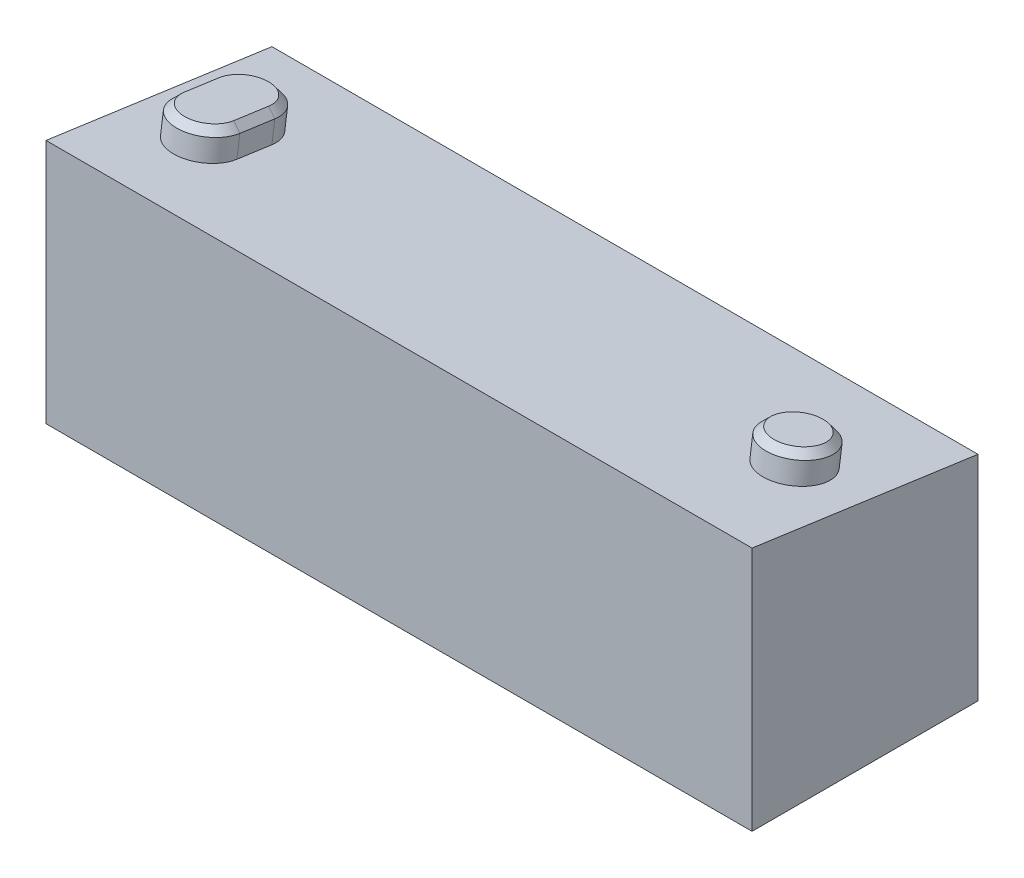
SolidWorks part; units mm, degrees
material "AISI 1010 钢，热轧条材"
ref_plane "前视基准面" through (0, 0, 0) normal (0, 0, 1) x (1, 0, 0)
ref_plane "上视基准面" through (0, 0, 0) normal (0, 1, 0) x (1, 0, 0)
ref_plane "右视基准面" through (0, 0, 0) normal (1, 0, 0) x (0, 0, -1)
sketch "草图1" plane through (0, 0, 0) normal (0, 0, 1) x (1, 0, 0)
  line L0 (-17, 0) -> (-17, -66.8639)
  line L1 (-20.5, 0) -> (-20.5, -66.8639)
  line L2 (-17, -66.8639) -> (-20.5, -66.8639)
  line L3 (0, 4.1737) -> (0, 50004.1737) construction
  line L4 (17, -66.8639) -> (20.5, -66.8639)
  line L5 (20.5, 0) -> (20.5, -66.8639)
  line L6 (17, 0) -> (17, -66.8639)
  arc A0 (17, 0) -> (-17, 0) centre (0, 0) ccw
  arc A1 (20.5, 0) -> (-20.5, 0) centre (0, 0) ccw
  circle A3 centre (0, 0) radius 20.5 construction
  circle A4 centre (0, 0) radius 17 construction
  point P4 (16.2572, 4.9703)
  point P15 (20.5, 0)
  dimension "D1" = 34
  dimension "D2" = 3.5
extrude "凸台-拉伸1" add sketch "草图1" along normal mid plane 32
sketch "草图2" plane through (0, 0, 0) normal (1, 0, 0) x (0, 0, -1)
  line L0 (0, 0) -> (50000, 0) construction
  line L1 (0, 0) -> (0, -50000) construction
  line L2 (29.9617, -44.7108) -> (0, -40.5) construction
  line L3 (16, -42.7487) -> (-16, -38.2513)
  line L4 (16, -66.8639) -> (16, 0) construction
  line L5 (-16, -66.8639) -> (-16, 0) construction
  line L6 (-16, -38.2513) -> (-16, -66.8639)
  line L7 (-16, -66.8639) -> (16, -66.8639)
  line L8 (16, -66.8639) -> (16, -42.7487)
  dimension "D1" = 8
  dimension "D2" = 40.5
extrude "切除-拉伸1" cut sketch "草图2" against normal mid plane 100
sketch "草图3" plane through (-20.5, 0, 0) normal (-1, 0, 0) x (0, 0, 1)
  line L0 (-16, -42.7487) -> (16, -38.2513)
  line L1 (-16, -39.2143) -> (16, -34.717)
  line L4 (-16, -42.7487) -> (-16, -39.2143)
  line L5 (16, -38.2513) -> (16, -34.717)
  line L7 (-16.4871, -39.2827) -> (15.5129, -34.7854) construction
  dimension "D1" = 3.5
extrude "凸台-拉伸2" add sketch "草图3" along normal blind 28.5
mirror "镜向1" about plane through (0, 0, 0) normal (1, 0, 0) of "凸台-拉伸2"
sketch "草图4" plane through (0, -36.2496, 5.0946) normal (0, 0.9903, -0.1392) x (1, 0, 0)
  line L0 (0, 0) -> (0, -50000) construction
  line L1 (-49, 5.1446) -> (49, 5.1446) construction
  line L2 (-49, -11.0126) -> (-49, 21.3019) construction
  line L3 (49, -11.0126) -> (49, 21.3019) construction
  line L4 (-40.5, 21.3019) -> (-40.5, -11.0126) construction
  line L5 (-49, 21.3019) -> (-20.5, 21.3019) construction
  line L6 (-49, -11.0126) -> (-20.5, -11.0126) construction
  line L7 (40.5, 21.3019) -> (40.5, -11.0126) construction
  line L8 (-36, 7.6446) -> (-36, 2.6446)
  line L9 (-45, 7.6446) -> (-45, 2.6446)
  arc A0 (-36, 7.6446) -> (-45, 7.6446) centre (-40.5, 7.6446) ccw
  arc A1 (-45, 2.6446) -> (-36, 2.6446) centre (-40.5, 2.6446) ccw
  circle A2 centre (40.5, 5.1446) radius 4.5
  dimension "D2" = 9
  dimension "D4" = 9
  dimension "D1" = 81
  dimension "D3" = 5
extrude "切除-拉伸2" cut sketch "草图4" against normal blind 28.5
sketch "草图5" plane through (0, 0, 0) normal (1, 0, 0) x (0, 0, -1)
  line L0 (16, -42.7487) -> (-16, -38.2513)
  line L1 (-16, -38.2513) -> (-16, -72.9987)
  line L2 (-16, -72.9987) -> (16, -72.9987)
  line L3 (16, -72.9987) -> (16, -42.7487)
  dimension "D1" = 30.25
extrude "凸台-拉伸3" add sketch "草图5" along normal mid plane 100 separate body
sketch "草图6" plane through (0, -39.7155, 5.5817) normal (0, 0.9903, -0.1392) x (1, 0, 0)
  line L2 (-36, 2.6446) -> (-36, 7.6446)
  line L3 (-36, 2.6446) -> (-36, 7.6446)
  line L4 (0, 0) -> (0, 49.0498) construction
  line L5 (-45, 7.6446) -> (-45, 2.6446)
  line L6 (-45, 7.6446) -> (-45, 2.6446)
  circle A0 centre (40.5, 5.1446) radius 4.5
  arc A2 (-36, 7.6446) -> (-45, 7.6446) centre (-40.5, 7.6446) ccw
  arc A3 (-36, 7.6446) -> (-45, 7.6446) centre (-40.5, 7.6446) ccw
  arc A5 (-45, 2.6446) -> (-36, 2.6446) centre (-40.5, 2.6446) ccw
  arc A6 (-45, 2.6446) -> (-36, 2.6446) centre (-40.5, 2.6446) ccw
  dimension "D1" = 0
  dimension "D2" = 0
  dimension "D3" = 0
  dimension "D4" = 0
extrude "凸台-拉伸4" add sketch "草图6" along normal blind 4
sketch "草图8" plane through (0, 0, 0) normal (1, 0, 0) x (0, 0, -1)
  line L0 (16, -42.7487) -> (-16, -38.2513)
  line L1 (-16, -38.2513) -> (-16, 32.2935)
  line L2 (-16, 32.2935) -> (16, 32.2935)
  line L3 (16, 32.2935) -> (16, -42.7487)
extrude "切除-拉伸3" cut sketch "草图8" against normal mid plane 120
chamfer "倒角1" distance 1 angle 45 5 edges at (40.5, -35.8442, 4.3866) (-40.5, -37.4447, -7.0015) (-45, -36.4705, -0.0696) (-36, -36.4705, -0.0696) (-40.5, -35.4963, 6.8623)
